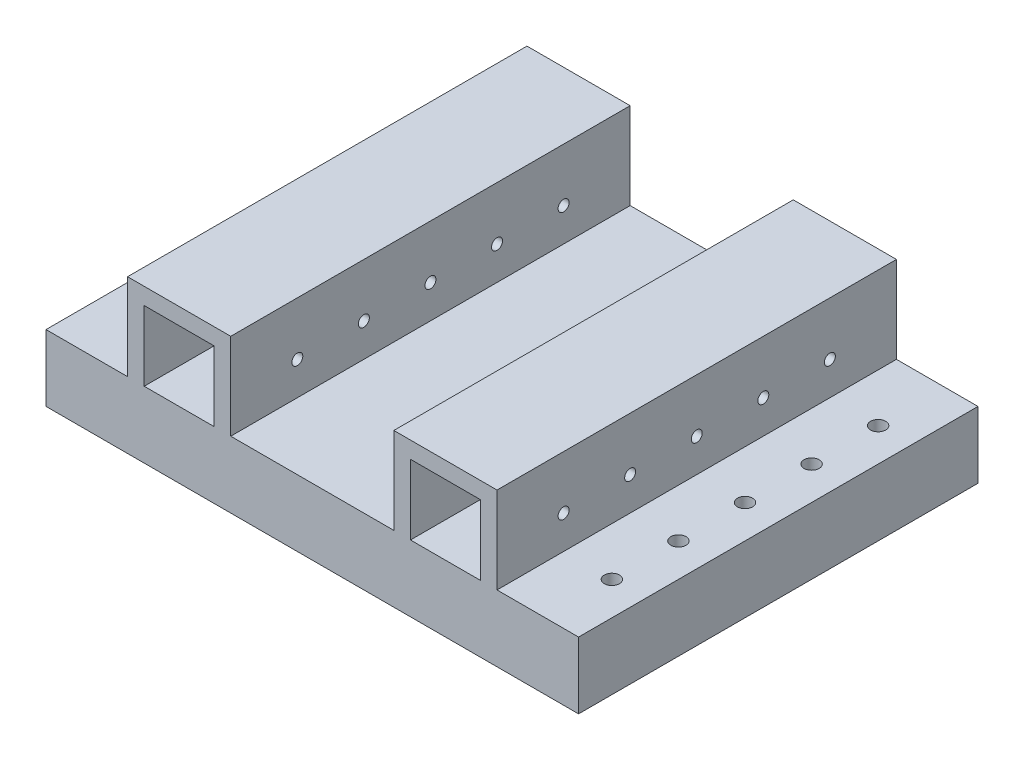
SolidWorks part; units mm, degrees
ref_plane "前视基准面" through (0, 0, 0) normal (0, 0, 1) x (1, 0, 0)
ref_plane "上视基准面" through (0, 0, 0) normal (0, 1, 0) x (1, 0, 0)
ref_plane "右视基准面" through (0, 0, 0) normal (1, 0, 0) x (0, 0, -1)
other "Configuration Table"
sketch "草图1" plane through (0, 0, 0) normal (0, 0, 1) x (1, 0, 0)
  line L0 (-80, 0) -> (80, 0)
  line L1 (80, 0) -> (80, 20)
  line L2 (80, 20) -> (55.5, 20)
  line L3 (55.5, 20) -> (55.5, 46)
  line L4 (55.5, 46) -> (24.5, 46)
  line L5 (24.5, 46) -> (24.5, 20)
  line L6 (24.5, 20) -> (-24.5, 20)
  line L7 (0, -55) -> (0, 55) construction
  line L8 (29.5, 41) -> (50.5, 41)
  line L9 (29.5, 41) -> (29.5, 20)
  line L10 (29.5, 20) -> (50.5, 20)
  line L11 (50.5, 41) -> (50.5, 20)
  line L12 (29.5, 41) -> (50.5, 20) construction
  line L13 (29.5, 20) -> (50.5, 41) construction
  line L14 (-29.5, 20) -> (-50.5, 41) construction
  line L15 (-29.5, 41) -> (-50.5, 20) construction
  line L16 (-50.5, 41) -> (-50.5, 20)
  line L17 (-29.5, 20) -> (-50.5, 20)
  line L18 (-29.5, 41) -> (-29.5, 20)
  line L19 (-29.5, 41) -> (-50.5, 41)
  line L20 (-24.5, 46) -> (-24.5, 20)
  line L21 (-55.5, 46) -> (-24.5, 46)
  line L22 (-55.5, 20) -> (-55.5, 46)
  line L23 (-80, 20) -> (-55.5, 20)
  line L24 (-80, 0) -> (-80, 20)
  point P0 (-40, 30.5)
  point P3 (40, 30.5)
  point P29 (0, 20)
  point P34 (0, 0)
  dimension "D1" = 80
  dimension "D2" = 20
  dimension "D3" = 20
  dimension "D4" = 31
  dimension "D5" = 5
  dimension "D6" = 21
  dimension "D7" = 21
  dimension "D9" = 5
  dimension "D10" = 29.5
extrude "凸台-拉伸1" add sketch "草图1" along normal blind 120
sketch "草图2" plane through (0, 0, 0) normal (0, -1, 0) x (1, 0, 0)
  line L0 (-80, 60) -> (80, 60) construction
  line L1 (-80, 120) -> (-80, 0) construction
  line L2 (80, 120) -> (80, 0) construction
  line L3 (0, 120) -> (0, 0) construction
  line L4 (-80, 120) -> (80, 120) construction
  line L5 (-80, 0) -> (80, 0) construction
  line L7 (-42.5, 97) -> (42.5, 97)
  line L8 (-42.5, 97) -> (-42.5, 23)
  line L9 (-42.5, 23) -> (42.5, 23)
  line L10 (42.5, 97) -> (42.5, 23)
  line L11 (-42.5, 97) -> (42.5, 23) construction
  line L12 (-42.5, 23) -> (42.5, 97) construction
  point P12 (0, 60)
  dimension "D1" = 74
  dimension "D2" = 85
extrude "切除-拉伸1" cut sketch "草图2" against normal blind 16
sketch "草图3" plane through (-55.5, 0, 0) normal (-1, 0, 0) x (0, 0, 1)
  line L0 (120, 20) -> (0, 20) construction
  line L1 (0, 46) -> (0, 20) construction
  circle A0 centre (20, 30) radius 1.65
  circle A1 centre (40, 30) radius 1.65
  circle A2 centre (60, 30) radius 1.65
  circle A3 centre (80, 30) radius 1.65
  circle A4 centre (100, 30) radius 1.65
  dimension "D1" = 3.3
  dimension "D2" = 20
  dimension "D4" = 10
  dimension "D3" = 5
extrude "切除-拉伸2" cut sketch "草图3" against normal through all
sketch "草图5" plane through (0, 0, 0) normal (0, -1, 0) x (1, 0, 0)
  line L0 (0, 0) -> (0, 25.3851) construction
  line L1 (-80, 0) -> (80, 0) construction
  line L2 (-80, 120) -> (-80, 0) construction
  line L3 (-80, 120) -> (80, 120) construction
  circle A0 centre (-70, 100) radius 2.2755
  circle A1 centre (-70, 80) radius 2.2755
  circle A2 centre (-70, 60) radius 2.2755
  circle A3 centre (-70, 40) radius 2.2755
  circle A4 centre (-70, 20) radius 2.2755
  dimension "D1" = 10
  dimension "D2" = 20
  dimension "D3" = 5
extrude "切除-拉伸3" cut sketch "草图5" against normal through all
mirror "镜向1" about plane through (0, 0, 0) normal (1, 0, 0) of "切除-拉伸3"
